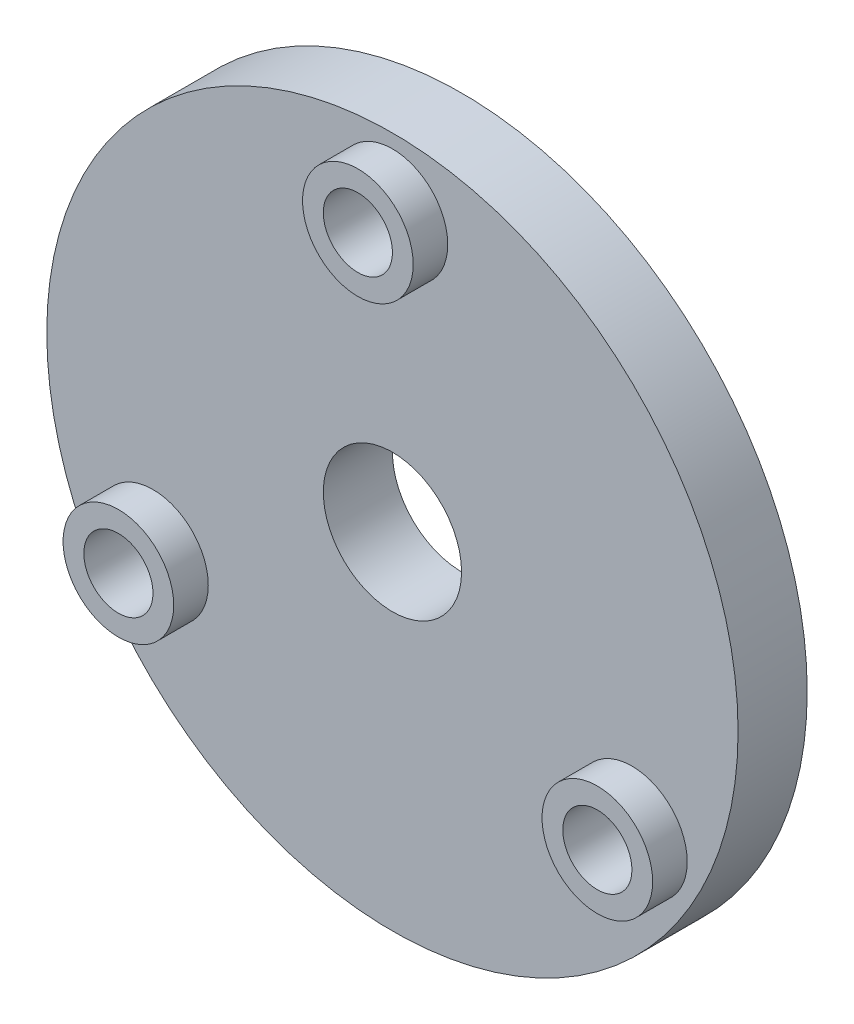
SolidWorks part; units mm, degrees
ref_plane "Front Plane" through (0, 0, 0) normal (0, 0, 1) x (1, 0, 0)
ref_plane "Top Plane" through (0, 0, 0) normal (0, 1, 0) x (1, 0, 0)
ref_plane "Right Plane" through (0, 0, 0) normal (1, 0, 0) x (0, 0, -1)
sketch "Sketch1" plane through (0, 0, 0) normal (0, 0, 1) x (1, 0, 0)
  circle A0 centre (0, 0) radius 50
  circle A3 centre (0, 0) radius 10
  dimension "D1" = 100
extrude "Boss-Extrude2" add sketch "Sketch1" along normal blind 10
sketch "Sketch3" plane through (0, 0, 0) normal (0, 0, 1) x (1, 0, 0)
  line L0 (0, 0) -> (0, 40) construction
  circle A0 centre (0, 40) radius 5
extrude "Cut-Extrude2" cut sketch "Sketch3" along normal blind 10
pattern_circular "CirPattern1" count 3 over 360 about axis through (0, 0, 0) along (0, 0, 1) of "Cut-Extrude2"
sketch "Sketch4" plane through (0, 0, 10) normal (0, 0, 1) x (1, 0, 0)
  line L0 (0, 0) -> (0, 40) construction
  circle A0 centre (0, 40) radius 8
  circle A1 centre (0, 40) radius 5
extrude "Boss-Extrude3" add sketch "Sketch4" along normal blind 5
pattern_circular "CirPattern2" count 3 over 360 about axis through (0, 0, 0) along (0, 0, 1) of "Boss-Extrude3"
